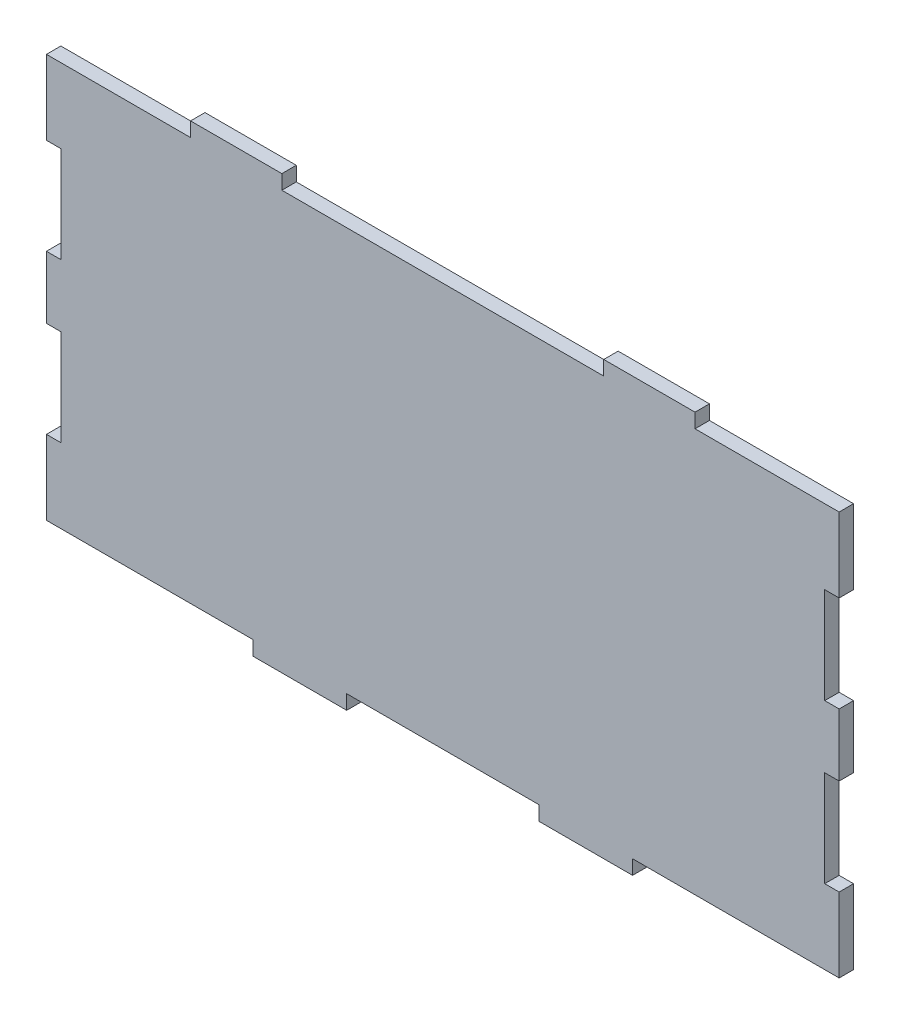
SolidWorks part; units mm, degrees
ref_plane "Plan de face" through (0, 0, 0) normal (0, 0, 1) x (1, 0, 0)
ref_plane "Plan de dessus" through (0, 0, 0) normal (0, 1, 0) x (1, 0, 0)
ref_plane "Plan de droite" through (0, 0, 0) normal (1, 0, 0) x (0, 0, -1)
sketch "Esquisse1" plane through (0, 0, 0) normal (0, 0, 1) x (1, 0, 0)
  line L1 (0, 0) -> (-330, 0)
  line L2 (0, 0) -> (0, 180)
  line L3 (0, 180) -> (-330, 180)
  line L4 (-330, 0) -> (-330, 180)
  dimension "D1" = 180
  dimension "D2" = 330
extrude "Boss.-Extru.1" add sketch "Esquisse1" along normal blind 6
sketch "Esquisse2" plane through (0, 0, 6) normal (0, 0, 1) x (1, 0, 0)
  line L0 (-330, 180) -> (-330, 0) construction
  line L1 (-330, 180) -> (-270, 180)
  line L2 (-330, 180) -> (-330, 174)
  line L3 (-330, 174) -> (-270, 174)
  line L4 (-270, 180) -> (-270, 174)
  line L5 (0, 180) -> (-330, 180) construction
  line L6 (0, 0) -> (0, 180) construction
  line L7 (-232, 180) -> (-98, 180)
  line L8 (-232, 180) -> (-232, 174)
  line L9 (-232, 174) -> (-98, 174)
  line L10 (-98, 180) -> (-98, 174)
  line L11 (0, 180) -> (-60, 180)
  line L12 (0, 180) -> (0, 174)
  line L13 (0, 174) -> (-60, 174)
  line L14 (-60, 180) -> (-60, 174)
  line L15 (-330, 143) -> (-324, 143)
  line L16 (-330, 143) -> (-330, 103)
  line L17 (-330, 103) -> (-324, 103)
  line L18 (-324, 143) -> (-324, 103)
  line L19 (-330, 37) -> (-324, 37)
  line L20 (-330, 37) -> (-330, 77)
  line L21 (-330, 77) -> (-324, 77)
  line L22 (-324, 37) -> (-324, 77)
  line L23 (0, 143) -> (-6, 143)
  line L24 (0, 143) -> (0, 103)
  line L25 (0, 103) -> (-6, 103)
  line L26 (-6, 143) -> (-6, 103)
  line L27 (-330, 0) -> (0, 0) construction
  line L28 (0, 77) -> (-6, 77)
  line L29 (0, 77) -> (0, 37)
  line L30 (0, 37) -> (-6, 37)
  line L31 (-6, 77) -> (-6, 37)
  line L32 (-330, 0) -> (-244, 0)
  line L33 (-330, 0) -> (-330, 6)
  line L34 (-330, 6) -> (-244, 6)
  line L35 (-244, 0) -> (-244, 6)
  line L36 (-205, 6) -> (-125, 6)
  line L37 (-205, 6) -> (-205, 0)
  line L38 (-205, 0) -> (-125, 0)
  line L39 (-125, 6) -> (-125, 0)
  line L41 (-86, 6) -> (0, 6)
  line L42 (-86, 6) -> (-86, 0)
  line L43 (-86, 0) -> (0, 0)
  line L44 (0, 6) -> (0, 0)
  dimension "D1" = 60
  dimension "D2" = 6
  dimension "D3" = 6
  dimension "D4" = 38
  dimension "D5" = 6
  dimension "D6" = 60
  dimension "D7" = 38
  dimension "D8" = 37
  dimension "D9" = 40
  dimension "D10" = 26
  dimension "D11" = 6
  dimension "D12" = 6
  dimension "D13" = 40
  dimension "D14" = 37
  dimension "D15" = 40
  dimension "D16" = 26
  dimension "D17" = 40
  dimension "D18" = 6
  dimension "D19" = 6
  dimension "D20" = 86
  dimension "D21" = 80
  dimension "D22" = 86
  dimension "D23" = 39
  dimension "D24" = 6
  dimension "D25" = 6
  dimension "D26" = 6
extrude "Enlèv. mat encoche" cut sketch "Esquisse2" against normal through all
